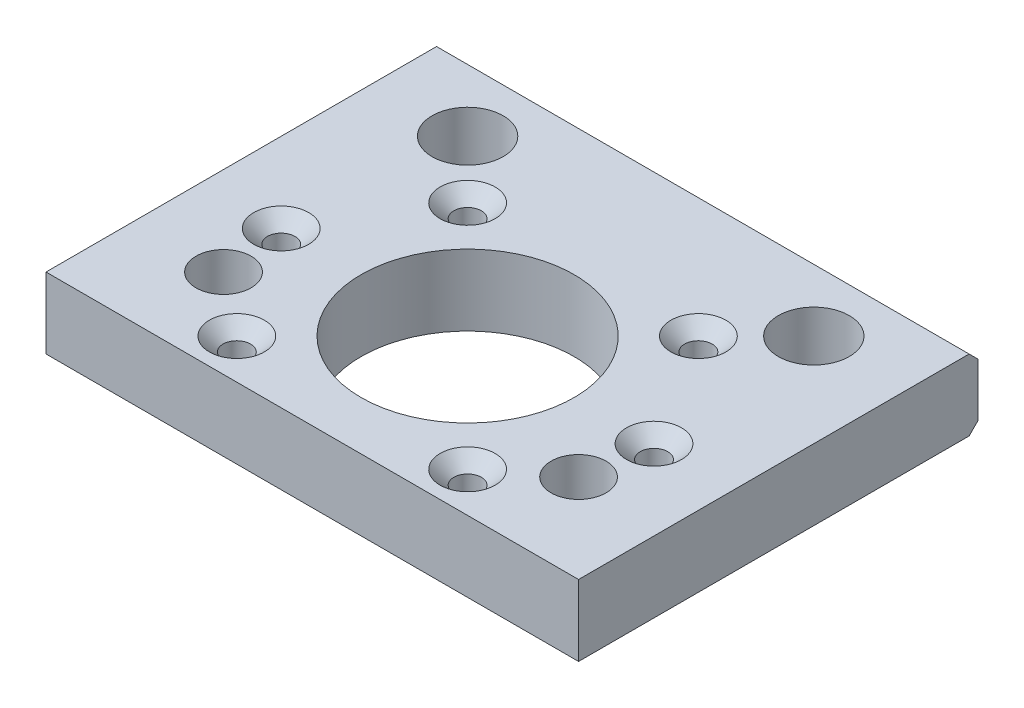
SolidWorks part; units mm, degrees
ref_plane "前视基准面" through (0, 0, 0) normal (0, 0, 1) x (1, 0, 0)
ref_plane "上视基准面" through (0, 0, 0) normal (0, 1, 0) x (1, 0, 0)
ref_plane "右视基准面" through (0, 0, 0) normal (1, 0, 0) x (0, 0, -1)
sketch "草图1" plane through (0, 0, 0) normal (0, 1, 0) x (1, 0, 0)
  line L0 (0, -55) -> (0, 55) construction
  line L1 (-30, 22.5) -> (30, 22.5)
  line L2 (-30, 22.5) -> (-30, -22.5)
  line L3 (-30, -22.5) -> (30, -22.5)
  line L4 (30, 22.5) -> (30, -22.5)
  circle A0 centre (-20, -12.5) radius 2.5
  circle A1 centre (20, -12.5) radius 2.5
  circle A2 centre (0, -5) radius 12
  point P4 (0, 22.5)
  point P5 (30, 0)
  dimension "D3" = 5
  dimension "D6" = 24
  dimension "D1" = 60
  dimension "D2" = 45
  dimension "D4" = 10
  dimension "D5" = 10
  dimension "D9" = 17.5
extrude "凸台-拉伸1" add sketch "草图1" along normal blind 8
chamfer "倒角1" distance 1 angle 45 4 edges at (30, 4, -22.5) (0, 8, -22.5) (-30, 4, -22.5) (0, 0, -22.5)
sketch "草图2" plane through (0, 8, 0) normal (0, 1, 0) x (1, 0, 0)
  line L0 (-30, 21.5) -> (-30, -22.5) construction
  line L1 (-30, -22.5) -> (30, -22.5) construction
  line L2 (0, -4.4) -> (0, 4.4) construction
  circle A0 centre (-19.5, 14.5) radius 4
  circle A1 centre (19.5, 14.5) radius 4
  dimension "D1" = 10.5
  dimension "D3" = 8
  dimension "D2" = 37
extrude "切除-拉伸1" cut sketch "草图2" against normal blind 6
sketch "草图3" plane through (0, 0, 0) normal (0, -1, 0) x (-1, 0, 0)
  line L0 (0, 4.4) -> (0, -4.4) construction
  line L1 (30, -22.5) -> (-30, -22.5) construction
  line L2 (0, 11.541) -> (0, -21.541) construction
  circle A0 centre (13, -18) radius 1.25
  circle A2 centre (-13, -18) radius 1.25
  circle A3 centre (13, 8) radius 1.25
  circle A4 centre (-13, 8) radius 1.25
  circle A5 centre (21, -5) radius 1.55
  circle A6 centre (-21, -5) radius 1.55
  circle A8 centre (0, -5) radius 12 construction
  circle A9 centre (0, -5) radius 12 construction
  point P23 (0, -5)
  dimension "D1" = 26
  dimension "D2" = 2.5
  dimension "D6" = 42
  dimension "D7" = 3.1
  dimension "D3" = 4.5
  dimension "D5" = 26
  dimension "D4" = 2
extrude "切除-拉伸2" cut sketch "草图3" against normal through all
hole_wizard "打孔尺寸(%根据十字)槽半沉头木螺钉的类型2" positions "3D草图1" profile "草图4" countersink size "M6" standard "GB" end condition through all
sketch3d "3D草图1"
  line L0 (20, 8, 12.5) -> (20, 0, 12.5) construction
  line L1 (-20, 8, 12.5) -> (-20, 0, 12.5) construction
  point P0 (20, 0, 12.5)
  point P4 (-20, 0, 12.5)
sketch "草图4" plane through (20, 0, 12.5) normal (1, 0, 0) x (0, 0, -1)
  line L0 (0, 0) -> (0, 8)
  line L1 (0, 8) -> (3.1, 8)
  line L2 (3.1, 8) -> (3.1, 3.5)
  line L3 (3.1, 3.5) -> (6.6, 0)
  line L5 (6.6, 0) -> (0, 0)
  line L6 (-3.1, 3.5) -> (-6.6, 0) construction
  line L11 (0, -6.35) -> (0, 107.95) construction
  dimension "通孔孔直径" = 6.2
  dimension "通孔孔深度" = 8
  dimension "近端锥形沉头孔直径" = 13.2
  dimension "近端锥形沉头孔角度" = 90
hole_wizard "打孔尺寸(%根据十字)槽半沉头木螺钉的类型2" positions "3D草图2" profile "草图5" countersink size "M3" standard "GB" end condition through all
sketch3d "3D草图2"
  line L0 (-13, 8, -8) -> (-13, 0, -8) construction
  line L1 (-13, 8, 18) -> (-13, 0, 18) construction
  line L2 (13, 8, 18) -> (13, 0, 18) construction
  line L3 (13, 8, -8) -> (13, 0, -8) construction
  line L4 (-21, 8, 5) -> (-21, 0, 5) construction
  line L5 (21, 8, 5) -> (21, 0, 5) construction
  point P0 (-13, 8, -8)
  point P4 (-13, 8, 18)
  point P8 (13, 8, 18)
  point P12 (13, 8, -8)
  point P17 (-21, 8, 5)
  point P21 (21, 8, 5)
sketch "草图5" plane through (-13, 8, -8) normal (1, 0, 0) x (0, 0, 1)
  line L0 (0, 0) -> (0, 8)
  line L1 (0, 8) -> (1.55, 8)
  line L2 (1.55, 8) -> (1.55, 1.55)
  line L3 (1.55, 1.55) -> (3.1, 0)
  line L5 (3.1, 0) -> (0, 0)
  line L6 (-1.55, 1.55) -> (-3.1, 0) construction
  line L11 (0, -6.35) -> (0, 107.95) construction
  dimension "通孔孔直径" = 3.1
  dimension "通孔孔深度" = 8
  dimension "近端锥形沉头孔直径" = 6.2
  dimension "近端锥形沉头孔角度" = 90
